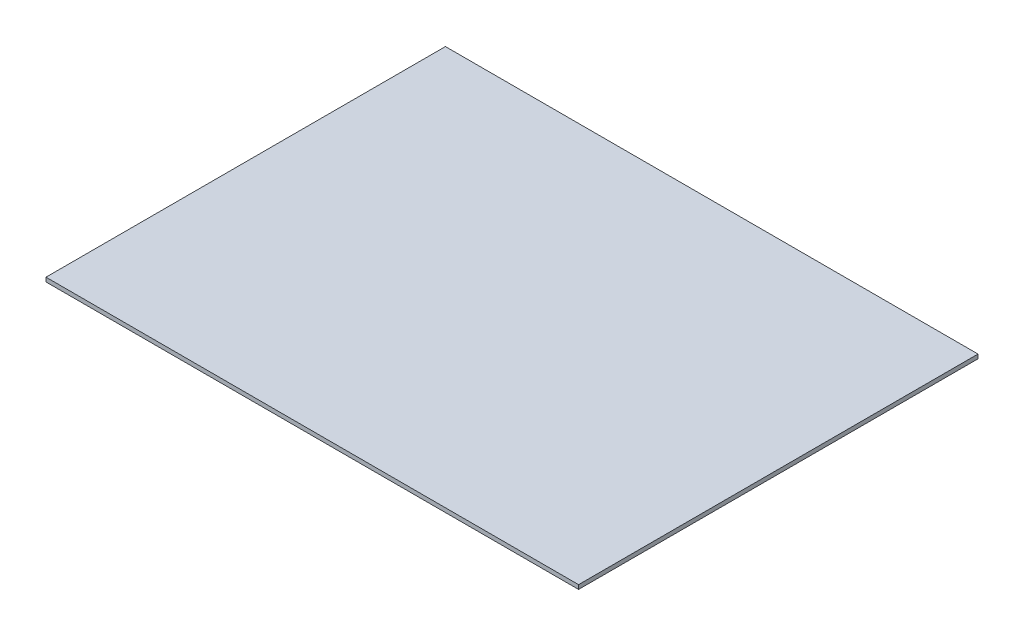
SolidWorks part; units mm, degrees
ref_plane "Front Plane" through (0, 0, 0) normal (0, 0, 1) x (1, 0, 0)
ref_plane "Top Plane" through (0, 0, 0) normal (0, 1, 0) x (1, 0, 0)
ref_plane "Right Plane" through (0, 0, 0) normal (1, 0, 0) x (0, 0, -1)
sketch "Sketch1" plane through (0, 0, 0) normal (0, 1, 0) x (1, 0, 0)
  line L0 (0, 0) -> (0, 304.8) construction
  line L1 (-203.2, 304.8) -> (203.2, 304.8)
  line L2 (-203.2, 0) -> (203.2, 0)
  line L3 (-203.2, 304.8) -> (-203.2, 0)
  line L4 (203.2, 0) -> (203.2, 304.8)
  point P6 (0, 304.8)
  point P9 (0, 0)
  dimension "D1" = 304.8
  dimension "D3" = 406.4
extrude "Boss-Extrude1" add sketch "Sketch1" along normal blind 3.175
sketch "Sketch2" plane through (0, 0, 0) normal (0, 0, 1) x (1, 0, 0)
  line L1 (-203.2, 3.175) -> (203.2, 3.175)
  line L2 (-203.2, 3.175) -> (-203.2, 0)
  line L3 (-203.2, 0) -> (203.2, 0)
  line L4 (203.2, 3.175) -> (203.2, 0)
